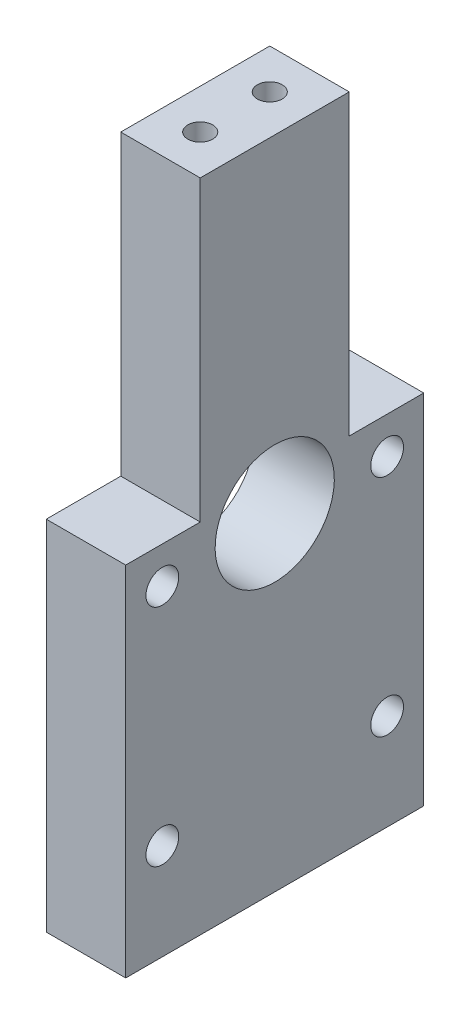
SolidWorks part; units mm, degrees
ref_plane "前视基准面" through (0, 0, 0) normal (0, 0, 1) x (1, 0, 0)
ref_plane "上视基准面" through (0, 0, 0) normal (0, 1, 0) x (1, 0, 0)
ref_plane "右视基准面" through (0, 0, 0) normal (1, 0, 0) x (0, 0, -1)
sketch "草图1" plane through (0, 0, 0) normal (0, 0, 1) x (1, 0, 0)
  line L5 (10, -11) -> (18, -11)
  line L6 (10, -11) -> (10, -77)
  line L7 (10, -77) -> (18, -77)
  line L8 (18, -11) -> (18, -77)
  dimension "D1" = 66
  dimension "D2" = 8
  dimension "D5" = 8
extrude "凸台-拉伸1" add sketch "草图1" along normal blind 30
sketch "草图7" plane through (10, 0, 0) normal (-1, 0, 0) x (0, 0, 1)
  line L0 (-8.7616, -71) -> (47.4785, -71) construction
  line L1 (30, -77) -> (0, -77) construction
  line L2 (15, -77) -> (15, -20.1889) construction
  line L3 (-1, -56) -> (31, -56) construction
  line L4 (15, -56) -> (26.3137, -44.6863) construction
  circle A0 centre (15, -56) radius 16 construction
  circle A2 centre (26.3137, -44.6863) radius 1.5
  circle A3 centre (3.6863, -44.6863) radius 1.5
  circle A4 centre (26.3137, -67.3137) radius 1.5
  circle A5 centre (3.6863, -67.3137) radius 1.5
  dimension "D2" = 32
  dimension "D3" = 15
  dimension "D5" = 3
  dimension "D1" = 6
  dimension "D4" = 45
extrude "切除-拉伸2" cut sketch "草图7" against normal blind 5
hole_wizard "M4 螺纹孔2" positions "3D草图6" profile "草图8" tap size "M4" standard "GB"
sketch3d "3D草图6"
  line L0 (15, -44.6863, 3.6863) -> (10, -44.6863, 3.6863) construction
  line L1 (15, -67.3137, 3.6863) -> (10, -67.3137, 3.6863) construction
  line L2 (15, -67.3137, 26.3137) -> (10, -67.3137, 26.3137) construction
  line L3 (15, -44.6863, 26.3137) -> (10, -44.6863, 26.3137) construction
  point P0 (18, -44.6863, 3.6863)
  point P4 (18, -67.3137, 3.6863)
  point P8 (18, -67.3137, 26.3137)
  point P12 (18, -44.6863, 26.3137)
sketch "草图8" plane through (18, -44.6863, 3.6863) normal (0, 1, 0) x (0, 0, -1)
  line L0 (0, 0) -> (0, 11.0914)
  line L1 (0, 11.0914) -> (1.65, 10.1)
  line L2 (1.65, 10.1) -> (1.65, 0)
  line L5 (1.65, 0) -> (0, 0)
  line L10 (0, 11.0914) -> (-1.65, 10.1) construction
  line L11 (0, -6.35) -> (0, 107.95) construction
  dimension "螺纹孔钻头直径" = 3.3
  dimension "螺纹孔钻头深度" = 10.1
  dimension "导头角度" = 118
cosmetic thread "孔螺蚊线5" parameters "D1"=8, "D2"=4
cosmetic thread "孔螺蚊线6" parameters "D1"=8, "D2"=4
cosmetic thread "孔螺蚊线7" parameters "D1"=8, "D2"=4
cosmetic thread "孔螺蚊线8" parameters "D1"=8, "D2"=4
sketch "草图10" plane through (0, -11, 0) normal (0, 1, 0) x (1, 0, 0)
  line L0 (18, -15) -> (10, -15) construction
  line L1 (18, -30) -> (18, 0) construction
  line L2 (10, -30) -> (10, 0) construction
  line L3 (14, 0) -> (14, -30) construction
  line L4 (18, 0) -> (10, 0) construction
  line L5 (18, -30) -> (10, -30) construction
  circle A0 centre (14, -11.5) radius 1
  circle A1 centre (14, -18.5) radius 1
  dimension "D3" = 2
  dimension "D4" = 2
  dimension "D1" = 3.5
  dimension "D2" = 3.5
extrude "切除-拉伸4" cut sketch "草图10" against normal blind 5
hole_wizard "M3 螺纹孔1" positions "3D草图7" profile "草图11" tap size "M3" standard "GB"
sketch3d "3D草图7"
  line L0 (14, -16, 11.5) -> (14, -11, 11.5) construction
  line L1 (14, -16, 18.5) -> (14, -11, 18.5) construction
  point P0 (14, -11, 11.5)
  point P4 (14, -11, 18.5)
sketch "草图11" plane through (14, -11, 11.5) normal (1, 0, 0) x (0, 0, 1)
  line L0 (0, 0) -> (0, 11.2511)
  line L1 (0, 11.2511) -> (1.25, 10.5)
  line L2 (1.25, 10.5) -> (1.25, 0)
  line L5 (1.25, 0) -> (0, 0)
  line L10 (0, 11.2511) -> (-1.25, 10.5) construction
  line L11 (0, -6.35) -> (0, 107.95) construction
  dimension "螺纹孔钻头直径" = 2.5
  dimension "螺纹孔钻头深度" = 10.5
  dimension "导头角度" = 118
cosmetic thread "孔螺蚊线9" parameters "D1"=8, "D2"=3
cosmetic thread "孔螺蚊线10" parameters "D1"=8, "D2"=3
sketch "草图12" plane through (0, -77, 0) normal (0, -1, 0) x (1, 0, 0)
  line L0 (18, 15) -> (10, 15) construction
  line L1 (18, 30) -> (18, 0) construction
  line L2 (10, 30) -> (10, 0) construction
  line L3 (14, 30) -> (14, 0) construction
  line L4 (10, 30) -> (18, 30) construction
  line L5 (10, 0) -> (18, 0) construction
  circle A0 centre (14, 20) radius 1
  circle A1 centre (14, 10) radius 1
  dimension "D3" = 2
  dimension "D4" = 2
  dimension "D1" = 5
  dimension "D2" = 5
extrude "切除-拉伸5" cut sketch "草图12" against normal blind 5
hole_wizard "M3 螺纹孔2" positions "3D草图8" profile "草图13" tap size "M3" standard "GB"
sketch3d "3D草图8"
  line L0 (14, -72, 20) -> (14, -77, 20) construction
  line L1 (14, -72, 10) -> (14, -77, 10) construction
  point P0 (14, -77, 20)
  point P4 (14, -77, 10)
sketch "草图13" plane through (14, -77, 20) normal (1, 0, 0) x (0, 0, -1)
  line L0 (0, 0) -> (0, 19.2511)
  line L1 (0, 19.2511) -> (1.25, 18.5)
  line L2 (1.25, 18.5) -> (1.25, 0)
  line L5 (1.25, 0) -> (0, 0)
  line L10 (0, 19.2511) -> (-1.25, 18.5) construction
  line L11 (0, -6.35) -> (0, 107.95) construction
  dimension "螺纹孔钻头直径" = 2.5
  dimension "螺纹孔钻头深度" = 18.5
  dimension "导头角度" = 118
cosmetic thread "孔螺蚊线11" parameters "D1"=16, "D2"=3
cosmetic thread "孔螺蚊线12" parameters "D1"=16, "D2"=3
sketch "草图14" plane through (0, -11, 0) normal (0, 1, 0) x (1, 0, 0)
  line L0 (18, -15) -> (10, -15) construction
  line L1 (18, -30) -> (18, 0) construction
  line L2 (10, -30) -> (10, 0) construction
  line L4 (10, 0) -> (18, 0)
  line L5 (10, 0) -> (10, -7.5)
  line L6 (10, -7.5) -> (18, -7.5)
  line L7 (18, 0) -> (18, -7.5)
  line L8 (18, -30) -> (10, -30)
  line L9 (18, -30) -> (18, -22.5)
  line L10 (18, -22.5) -> (10, -22.5)
  line L11 (10, -30) -> (10, -22.5)
  dimension "D1" = 7.5
  dimension "D2" = 7.5
extrude "切除-拉伸6" cut sketch "草图14" against normal blind 30
sketch "草图15" plane through (18, 0, 0) normal (1, 0, 0) x (0, 0, -1)
  line L0 (-15, -11) -> (-15, -77) construction
  line L1 (-22.5, -11) -> (-7.5, -11) construction
  line L2 (-30, -77) -> (0, -77) construction
  circle A0 centre (-15, -44) radius 6
  dimension "D1" = 12
  dimension "D2" = 33
extrude "切除-拉伸7" cut sketch "草图15" against normal through all
